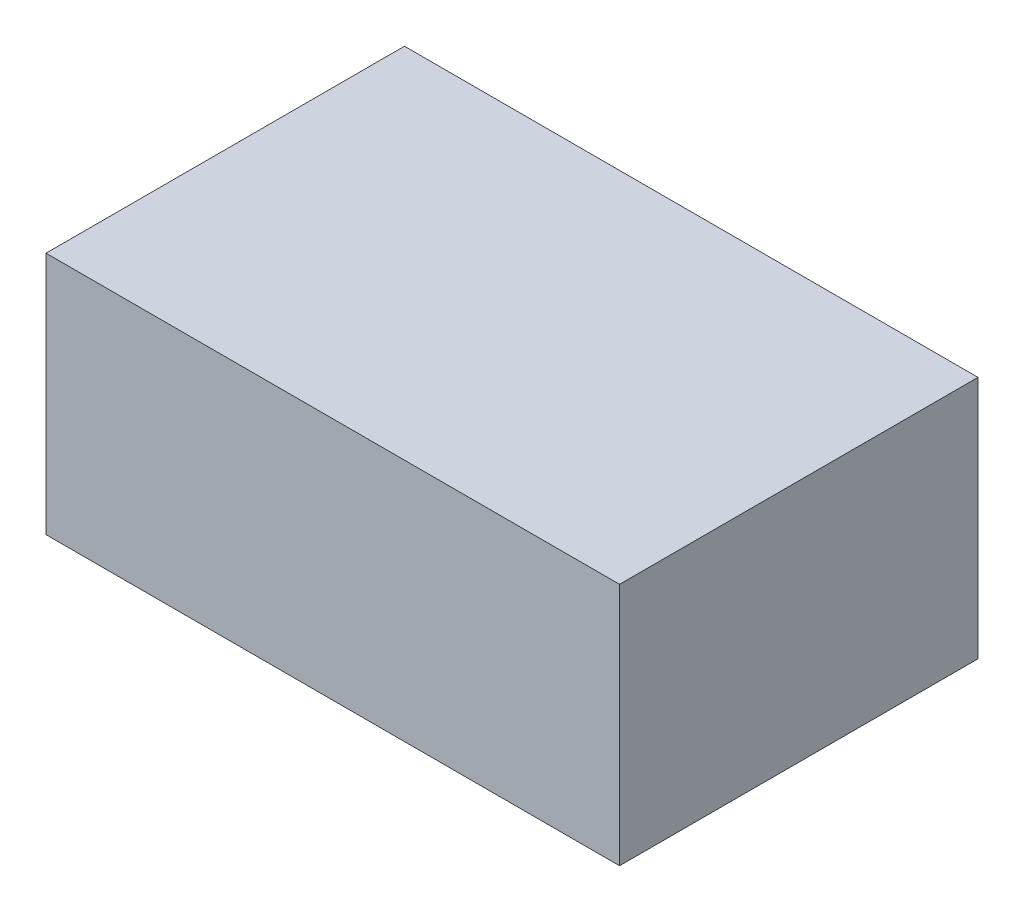
SolidWorks part; units mm, degrees
ref_plane "Front Plane" through (0, 0, 0) normal (0, 0, 1) x (1, 0, 0)
ref_plane "Top Plane" through (0, 0, 0) normal (0, 1, 0) x (1, 0, 0)
ref_plane "Right Plane" through (0, 0, 0) normal (1, 0, 0) x (0, 0, -1)
sketch "Sketch1" plane through (0, 0, 0) normal (0, 1, 0) x (1, 0, 0)
  line L0 (0, 0) -> (2, 0)
  line L1 (2, 0) -> (2, 1.25)
  line L2 (2, 1.25) -> (0, 1.25)
  line L3 (0, 1.25) -> (0, 0)
  dimension "D1" = 2
  dimension "D2" = 1.25
extrude "Boss-Extrude1" add sketch "Sketch1" along normal blind 0.85
